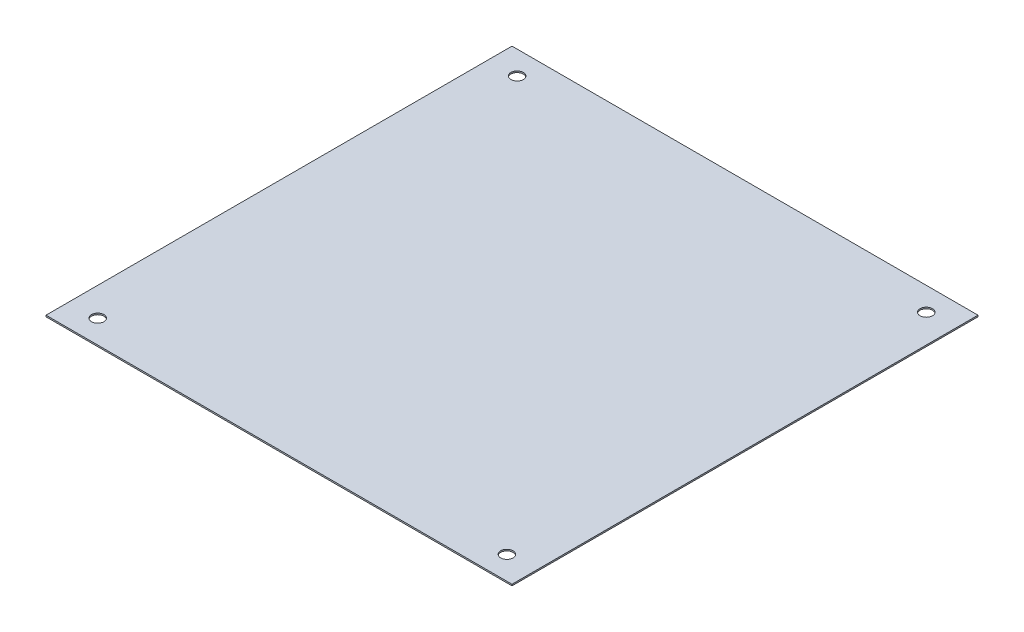
SolidWorks part; units mm, degrees
ref_plane "Front Plane" through (0, 0, 0) normal (0, 0, 1) x (1, 0, 0)
ref_plane "Top Plane" through (0, 0, 0) normal (0, 1, 0) x (1, 0, 0)
ref_plane "Right Plane" through (0, 0, 0) normal (1, 0, 0) x (0, 0, -1)
sketch "Sketch1" plane through (0, 0, 0) normal (0, 1, 0) x (1, 0, 0)
  line L1 (-127, -127) -> (127, -127)
  line L2 (-127, -127) -> (-127, 127)
  line L3 (-127, 127) -> (127, 127)
  line L4 (127, -127) -> (127, 127)
  line L5 (-127, -127) -> (127, 127) construction
  line L6 (-127, 127) -> (127, -127) construction
  line L7 (-111.506, -114.3) -> (111.506, -114.3) construction
  line L8 (-111.506, -114.3) -> (-111.506, 114.3) construction
  line L9 (-111.506, 114.3) -> (111.506, 114.3) construction
  line L10 (111.506, -114.3) -> (111.506, 114.3) construction
  line L11 (-111.506, -114.3) -> (111.506, 114.3) construction
  line L12 (-111.506, 114.3) -> (111.506, -114.3) construction
  circle A0 centre (-111.506, 114.3) radius 3.3782
  circle A1 centre (111.506, 114.3) radius 3.3782
  circle A2 centre (111.506, -114.3) radius 3.3782
  circle A3 centre (-111.506, -114.3) radius 3.3782
  point P0 (0, 0)
  point P6 (0, 0)
  dimension "D4" = 6.7564
  dimension "D1" = 254
  dimension "D2" = 228.6
  dimension "D3" = 223.012
extrude "Boss-Extrude1" add sketch "Sketch1" along normal blind 0.7937
